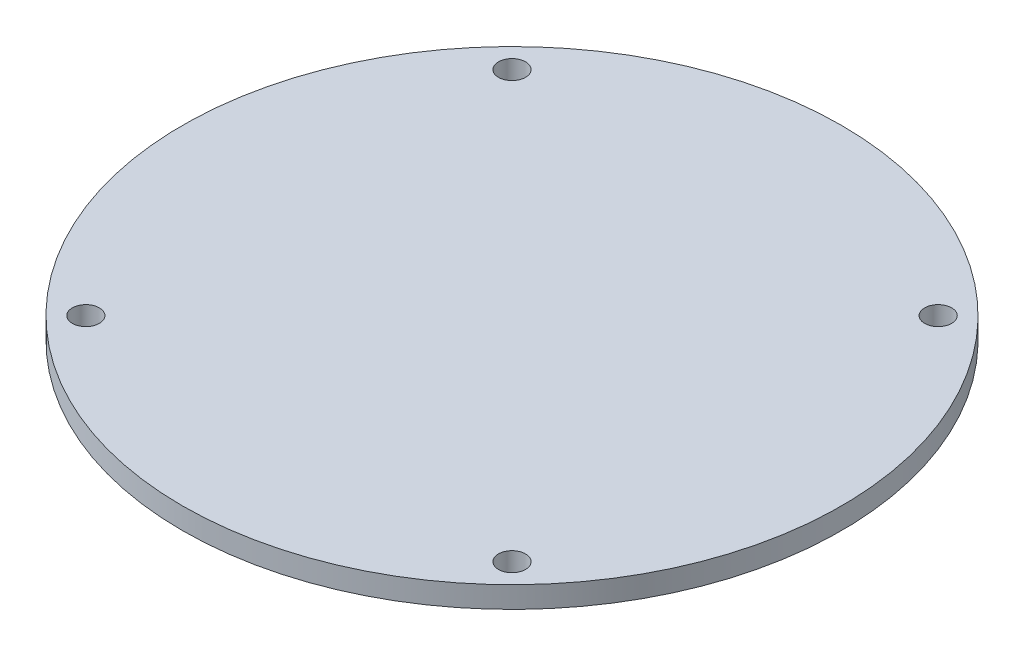
SolidWorks part; units mm, degrees
ref_plane "Front Plane" through (0, 0, 0) normal (0, 0, 1) x (1, 0, 0)
ref_plane "Top Plane" through (0, 0, 0) normal (0, 1, 0) x (1, 0, 0)
ref_plane "Right Plane" through (0, 0, 0) normal (1, 0, 0) x (0, 0, -1)
sketch "Sketch1" plane through (0, 0, 0) normal (0, 1, 0) x (1, 0, 0)
  line L0 (0, 0) -> (16.1645, 16.1645)
  circle A0 centre (0, 0) radius 25
  circle A1 centre (16.1645, 16.1645) radius 1.025
  circle A2 centre (16.1645, -16.1645) radius 1.025
  circle A3 centre (-16.1645, -16.1645) radius 1.025
  circle A4 centre (-16.1645, 16.1645) radius 1.025
  point P14 (0, 0)
  dimension "D1" = 50
  dimension "D3" = 2.05
  dimension "D2" = 22.86
  dimension "D4" = 4
extrude "Boss-Extrude1" add sketch "Sketch1" along normal blind 1.6256
